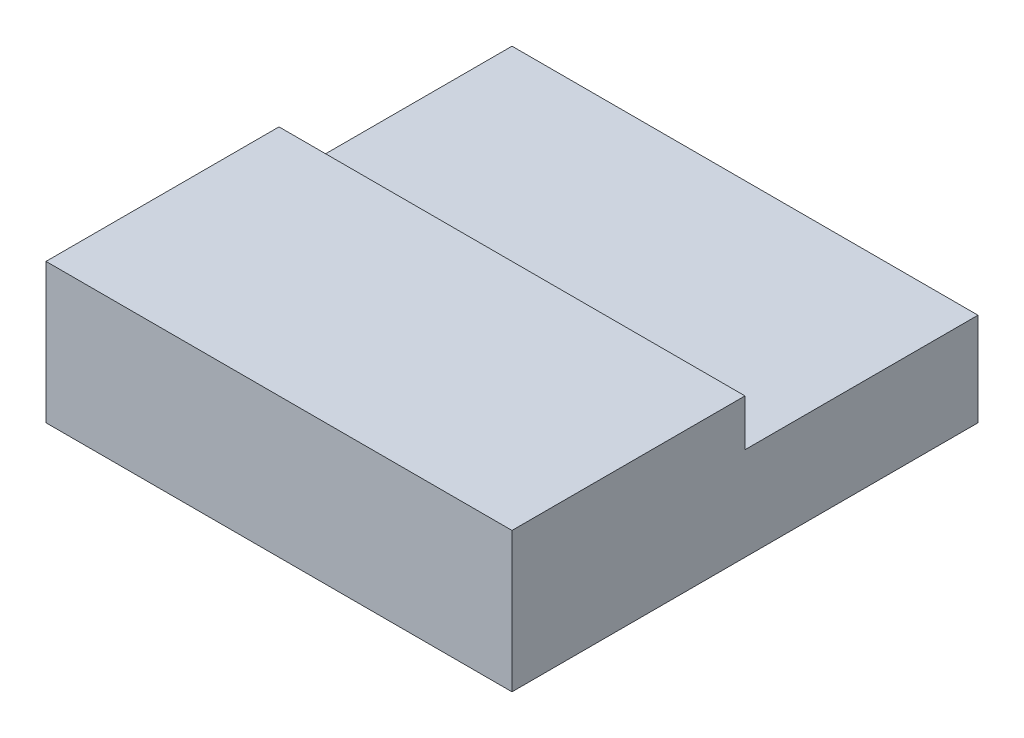
SolidWorks part; units mm, degrees
ref_plane "Front" through (0, 0, 0) normal (0, 0, 1) x (1, 0, 0)
ref_plane "Top" through (0, 0, 0) normal (0, 1, 0) x (1, 0, 0)
ref_plane "Right" through (0, 0, 0) normal (1, 0, 0) x (0, 0, -1)
sketch "Sketch1" plane through (0, 0, 0) normal (0, 1, 0) x (1, 0, 0)
  line L0 (0, 5.5461) -> (0, -3.2155) construction
  line L2 (-0.5, 0.5) -> (0.5, 0.5)
  line L3 (-0.5, 0.5) -> (-0.5, -0.5)
  line L4 (-0.5, -0.5) -> (0.5, -0.5)
  line L5 (-4.1375, 0) -> (5.7347, 0) construction
  line L6 (0.5, 0.5) -> (0.5, -0.5)
  point P9 (0, 0.5)
  point P10 (0.5, 0)
  dimension "D1" = 1
  dimension "D2" = 1
extrude "Boss-Extrude1" add sketch "Sketch1" along normal blind 0.3
sketch "Sketch2" plane through (0, 0.3, 0) normal (0, 1, 0) x (1, 0, 0)
  line L0 (0.5, -0.5) -> (0.5, 0.5) construction
  line L1 (-0.5, 0.5) -> (0.5, 0.5)
  line L2 (-0.5, 0.5) -> (-0.5, 0)
  line L3 (-0.5, 0) -> (0.5, 0)
  line L4 (0.5, 0.5) -> (0.5, 0)
extrude "Cut-Extrude1" cut sketch "Sketch2" against normal blind 0.1
sketch "Sketch3" plane through (0, 0, 0) normal (0, -1, 0) x (-1, 0, 0)
  line L0 (0, 0.5) -> (0, -0.5) construction
  line L1 (0.5, -0.5) -> (-0.5, -0.5) construction
  line L2 (-0.5, 0.5) -> (0.5, 0.5) construction
  point P4 (0, 0)
